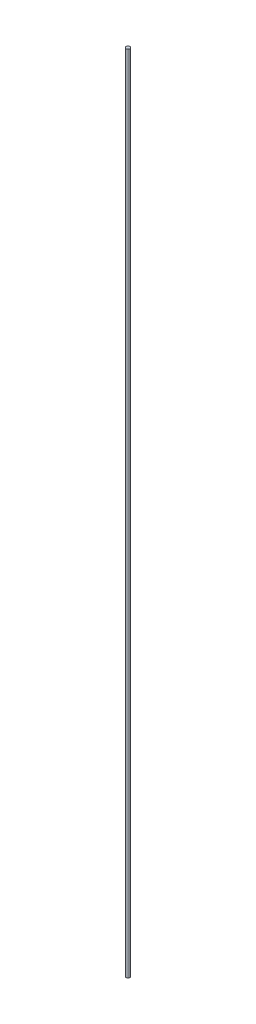
SolidWorks part; units mm, degrees
material "Brass"
ref_plane "Front Plane" through (0, 0, 0) normal (0, 0, 1) x (1, 0, 0)
ref_plane "Top Plane" through (0, 0, 0) normal (0, 1, 0) x (1, 0, 0)
ref_plane "Right Plane" through (0, 0, 0) normal (1, 0, 0) x (0, 0, -1)
sketch "Sketch1" plane through (0, 0, 0) normal (0, 1, 0) x (1, 0, 0)
  circle A0 centre (0, 0) radius 2.3813
  dimension "D1" = 4.7625
extrude "Boss-Extrude1" add sketch "Sketch1" along normal blind 1000
